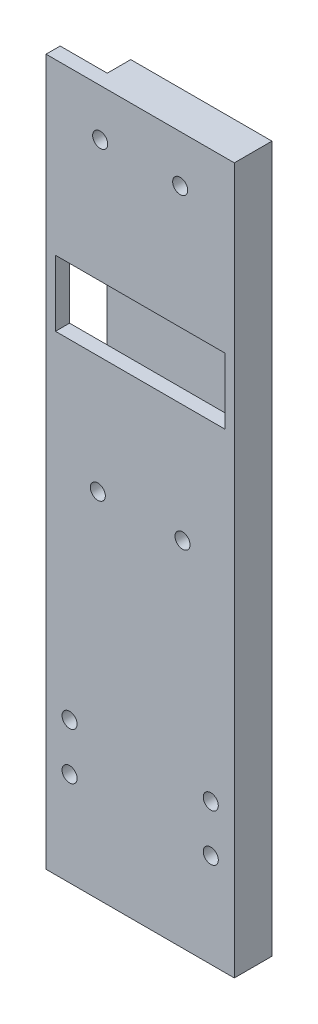
SolidWorks part; units mm, degrees
ref_plane "Front Plane" through (0, 0, 0) normal (0, 0, 1) x (1, 0, 0)
ref_plane "Top Plane" through (0, 0, 0) normal (0, 1, 0) x (1, 0, 0)
ref_plane "Right Plane" through (0, 0, 0) normal (1, 0, 0) x (0, 0, -1)
sketch "Sketch1" plane through (0, 0, 0) normal (0, 0, 1) x (1, 0, 0)
  line L0 (1.9048, -119.2857) -> (1.9048, -44.2857) construction
  line L1 (-18.0952, 30.7143) -> (21.9048, 30.7143)
  line L2 (-18.0952, 30.7143) -> (-18.0952, -119.2857)
  line L3 (-18.0952, -119.2857) -> (21.9048, -119.2857)
  line L4 (21.9048, 30.7143) -> (21.9048, -119.2857)
  circle A0 centre (-7.0952, -44.2857) radius 1.6
  circle A1 centre (10.9048, -44.2857) radius 1.6
  point P9 (1.9048, -44.2857)
  dimension "D1" = 40
  dimension "D2" = 150
extrude "Boss-Extrude1" add sketch "Sketch1" along normal blind 8 contours L4 L3 L2 L1
sketch "Sketch2" plane through (0, 0, 0) normal (0, 0, 1) x (1, 0, 0)
  line L0 (-18.0952, -119.2857) -> (21.9048, -119.2857) construction
  line L1 (-18.0952, 30.7143) -> (-8.0952, 30.7143)
  line L2 (-18.0952, 30.7143) -> (-18.0952, -119.2857)
  line L3 (-18.0952, -119.2857) -> (-8.0952, -119.2857)
  line L4 (-8.0952, 30.7143) -> (-8.0952, -119.2857)
  dimension "D1" = 10
extrude "Cut-Extrude1" cut sketch "Sketch2" along normal blind 5
sketch "Sketch5" plane through (0, 0, 8) normal (0, 0, 1) x (1, 0, 0)
  line L0 (1.9048, -119.2857) -> (1.9048, 20.7143) construction
  line L1 (-18.0952, -119.2857) -> (21.9048, -119.2857) construction
  line L2 (-6.5952, 20.7143) -> (10.4048, 20.7143)
  circle A0 centre (10.4048, 20.7143) radius 1.6
  circle A1 centre (-6.5952, 20.7143) radius 1.6
  point P7 (1.9048, 20.7143)
  dimension "D1" = 17
extrude "Cut-Extrude2" cut sketch "Sketch5" against normal blind 35 contours A0 | A1
sketch "Sketch6" plane through (0, 0, 8) normal (0, 0, 1) x (1, 0, 0)
  line L0 (1.9048, -119.2857) -> (1.9048, -19.2857) construction
  line L1 (-18.0952, -119.2857) -> (21.9048, -119.2857) construction
  line L2 (19.9048, -19.2857) -> (-16.0952, -19.2857)
  line L3 (-16.0952, -19.2857) -> (-16.0952, -5.2857)
  line L4 (-16.0952, -5.2857) -> (19.9048, -5.2857)
  line L5 (19.9048, -5.2857) -> (19.9048, -19.2857)
  point P7 (1.9048, -19.2857)
extrude "Cut-Extrude3" cut sketch "Sketch6" against normal blind 3
sketch "Sketch7" plane through (0, 0, 8) normal (0, 0, 1) x (1, 0, 0)
  circle A0 centre (-7.0952, -44.2857) radius 1.6
  circle A1 centre (10.9048, -44.2857) radius 1.6
extrude "Cut-Extrude4" cut sketch "Sketch7" against normal blind 10
sketch "Sketch8" plane through (0, 0, 8) normal (0, 0, 1) x (1, 0, 0)
  circle A0 centre (-13.0952, -89.2857) radius 1.6
  circle A1 centre (16.9048, -89.2857) radius 1.6
extrude "Cut-Extrude5" cut sketch "Sketch8" against normal blind 10
sketch "Sketch9" plane through (0, 0, 8) normal (0, 0, 1) x (1, 0, 0)
  circle A0 centre (-13.0952, -99.2857) radius 1.6
  circle A1 centre (16.9048, -99.2857) radius 1.6
extrude "Cut-Extrude6" cut sketch "Sketch9" against normal blind 10
